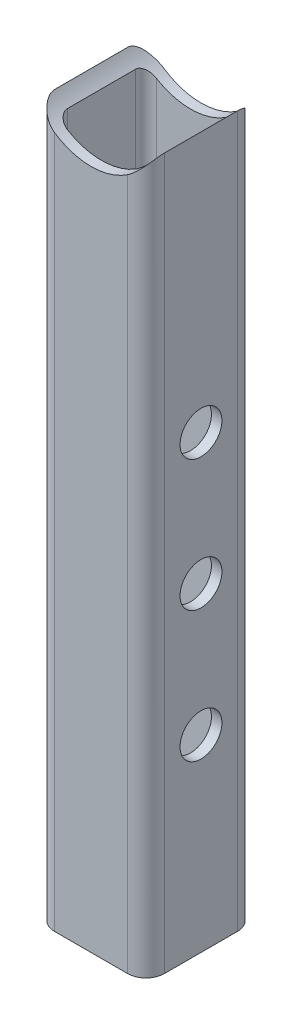
SolidWorks part; units mm, degrees
material "1060 Сплав"
ref_plane "Спереди" through (0, 0, 0) normal (0, 0, 1) x (1, 0, 0)
ref_plane "Сверху" through (0, 0, 0) normal (0, 1, 0) x (1, 0, 0)
ref_plane "Справа" through (0, 0, 0) normal (1, 0, 0) x (0, 0, -1)
sketch "Эскиз1" plane through (0, 0, 0) normal (0, 1, 0) x (1, 0, 0)
  line L1 (-6.993, -10.5) -> (6.993, -10.5)
  line L2 (-10.5, -6.993) -> (-10.5, 6.993)
  line L3 (-6.993, 10.5) -> (6.993, 10.5)
  line L4 (10.5, -6.993) -> (10.5, 6.993)
  line L5 (-10.5, -10.5) -> (10.5, 10.5) construction
  line L6 (-10.5, 10.5) -> (10.5, -10.5) construction
  line L7 (6.5, 8.5) -> (-6.5, 8.5)
  line L8 (8.5, 6.5) -> (8.5, -6.5)
  line L9 (6.5, -8.5) -> (-6.5, -8.5)
  line L10 (-8.5, 6.5) -> (-8.5, -6.5)
  line L11 (8.5, 8.5) -> (-8.5, -8.5) construction
  line L12 (8.5, -8.5) -> (-8.5, 8.5) construction
  arc A0 (-6.5, -8.5) -> (-8.5, -6.5) centre (-6.5, -6.5) cw
  arc A1 (8.5, 6.5) -> (6.5, 8.5) centre (6.5, 6.5) ccw
  arc A2 (-8.5, 6.5) -> (-6.5, 8.5) centre (-6.5, 6.5) cw
  arc A3 (6.5, -8.5) -> (8.5, -6.5) centre (6.5, -6.5) ccw
  arc A4 (-10.5, -6.993) -> (-6.993, -10.5) centre (-6.993, -6.993) ccw
  arc A5 (6.993, -10.5) -> (10.5, -6.993) centre (6.993, -6.993) ccw
  arc A6 (10.5, 6.993) -> (6.993, 10.5) centre (6.993, 6.993) ccw
  arc A7 (-10.5, 6.993) -> (-6.993, 10.5) centre (-6.993, 6.993) cw
  point P0 (0, 0)
  point P5 (0, 0)
  dimension "D4" = 2
  dimension "D5" = 2
  dimension "D6" = 3.507
  dimension "D1" = 21
  dimension "D2" = 21
  dimension "D3" = 17
extrude "Бобышка-Вытянуть1" add sketch "Эскиз1" along normal blind 140
sketch "Эскиз2" plane through (0, 0, -10.5) normal (0, 0, -1) x (-1, 0, 0)
  circle A0 centre (0, 142.5) radius 12.5
  dimension "D1" = 142.5
extrude "Вырез-Вытянуть1" cut sketch "Эскиз2" against normal through all
sketch "Эскиз3" plane through (10.5, 0, 0) normal (1, 0, 0) x (0, 0, -1)
  circle A0 centre (0, 36) radius 4
  circle A1 centre (0, 61) radius 4
  circle A2 centre (0, 86) radius 4
  dimension "D1" = 8
  dimension "D2" = 25
  dimension "D3" = 25
  dimension "D4" = 36
extrude "Вырез-Вытянуть2" cut sketch "Эскиз3" against normal through all
